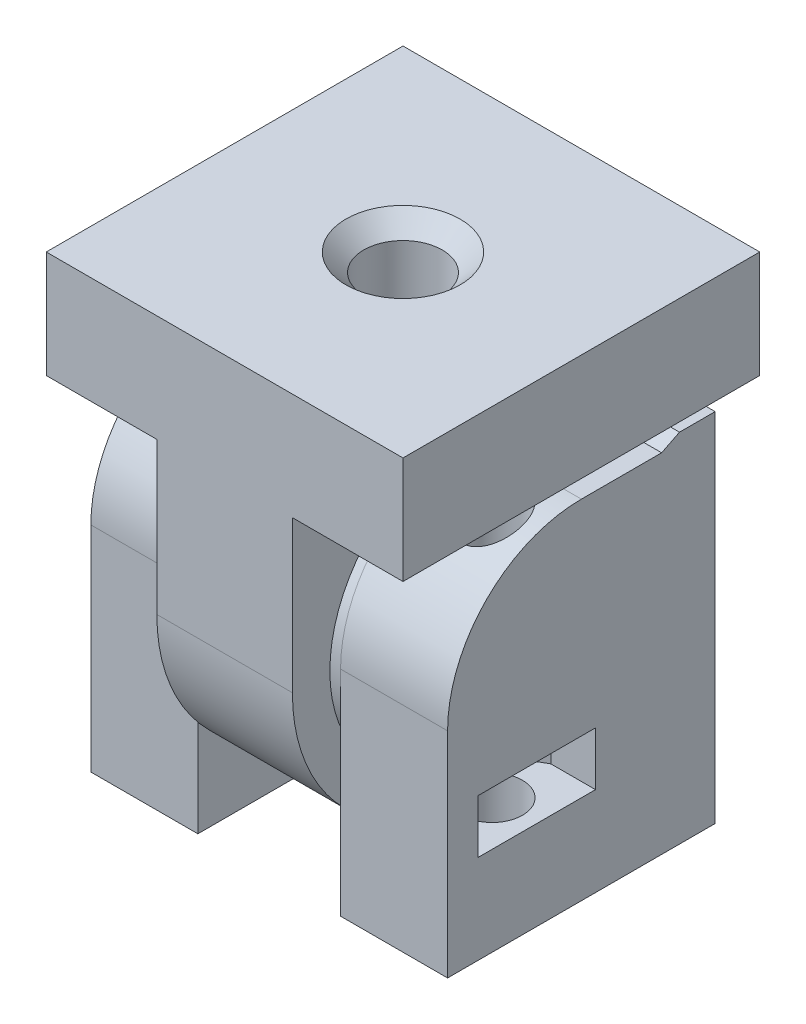
SolidWorks part; units mm, degrees
ref_plane "Front Plane" through (0, 0, 0) normal (0, 0, 1) x (1, 0, 0)
ref_plane "Top Plane" through (0, 0, 0) normal (0, 1, 0) x (1, 0, 0)
ref_plane "Right Plane" through (0, 0, 0) normal (1, 0, 0) x (0, 0, -1)
sketch "Sketch1" plane through (0, 0, 0) normal (1, 0, 0) x (0, 0, -1)
  circle A0 centre (0, 0) radius 7.5
  dimension "D1" = 15
extrude "Boss-Extrude1" add sketch "Sketch1" along normal blind 20
sketch "Sketch2" plane through (20, 0, 0) normal (1, 0, 0) x (0, 0, -1)
  line L5 (-7.5, 7.5) -> (7.5, 7.5)
  line L6 (-7.5, 7.5) -> (-7.5, -12)
  line L7 (-7.5, -12) -> (7.5, -12)
  line L8 (7.5, 7.5) -> (7.5, -12)
  circle A0 centre (0, 0) radius 7.5 construction
  point P0 (0, 0)
  point P6 (11.7696, -19.9449)
  point P7 (0, 7.5)
  point P10 (10, -14.5972)
  dimension "D1" = 12
extrude "Boss-Extrude2" add sketch "Sketch2" against normal blind 6
fillet "Fillet1" radius 7.5 1 edges at (17, 7.5, 7.5)
ref_plane "Plane3" through (10, 0, 0) normal (-1, 0, 0) x (0, 0, 1)
mirror "Mirror2" about plane through (10, 0, 0) normal (-1, 0, 0) of "Boss-Extrude2"
fillet "Fillet2" radius 7.5 1 edges at (3, 7.5, 7.5)
sketch "Sketch3" plane through (0, 7.5, 0) normal (0, 1, 0) x (1, 0, 0)
  line L0 (6, 7.5) -> (0, 7.5) construction
  line L1 (14, 7.5) -> (20, 7.5) construction
  circle A0 centre (3, -2.5) radius 1.7
  circle A1 centre (17, -2.5) radius 1.7
  point P6 (0, 0)
  point P9 (17, 7.5)
  point P10 (3, 7.5)
  dimension "D1" = 3.4
  dimension "D2" = 10
sketch "Sketch5" plane through (14, 0, 0) normal (-1, 0, 0) x (0, 0, 1)
  line L0 (10, 0) -> (10, 14.5)
  line L1 (10, 14.5) -> (-10, 14.5)
  line L2 (-7.5, 7.5) -> (0, 7.5) construction
  line L3 (-10, 0) -> (-10, 14.5)
  circle A0 centre (0, 0) radius 7.9
  circle A1 centre (0, 0) radius 7.5 construction
  circle A2 centre (0, 0) radius 10
  point P9 (13, 16.8825)
  line M5 (7.5, -12) -> (7.5, 0)
  line M15 (-7.5, 0) -> (-7.5, -12)
  dimension "D1" = 0.4
  dimension "D2" = 20
  dimension "D3" = 7
extrude "Boss-Extrude3" add sketch "Sketch5" along normal offset from surface (7.6 mm away) 0.2 from offset 0.2 separate body contours A2 A0 M15 M5 | A2 A0 M15 M5 | A2 L0 L1 L3 up to face at (6, -7.875, 0)
sketch "Sketch6" plane through (6.2, 0, 0) normal (-1, 0, 0) x (0, 0, 1)
  line L1 (10, 14.5) -> (-10, 14.5)
  line L2 (10, 14.5) -> (10, 8.5)
  line L3 (10, 8.5) -> (-10, 8.5)
  line L4 (-10, 14.5) -> (-10, 8.5)
  line L5 (-7.5, 7.5) -> (0, 7.5) construction
  line L7 (10, 14.5) -> (-10, 14.5) construction
  point P5 (-10.0218, 10.4)
  point P6 (-12.9171, 17)
  point P11 (-13, 17)
  dimension "D1" = 1
extrude "Boss-Extrude4" add sketch "Sketch6" along normal up to surface (6.2 mm away) contours L2 L1 L4 L3 up to face at (0, -1.4893, 0.3107)
sketch "Sketch7" plane through (13.8, 0, 0) normal (1, 0, 0) x (0, 0, -1)
  line L0 (-10, 0) -> (-10, 14.5) construction
  line L1 (10, 14.5) -> (-10, 14.5)
  line L2 (10, 14.5) -> (10, 8.5)
  line L3 (10, 8.5) -> (-10, 8.5)
  line L4 (-10, 14.5) -> (-10, 8.5)
  line L5 (7.5, 7.5) -> (0, 7.5) construction
  dimension "D1" = 1
extrude "Boss-Extrude5" add sketch "Sketch7" along normal up to surface (6.2 mm away) up to face at (20, -1.4893, 0.3107)
sketch "Sketch8" plane through (20, 0, 0) normal (1, 0, 0) x (0, 0, -1)
  line L0 (10, 14.5) -> (-10, 14.5) construction
  circle A0 centre (0, 11.5) radius 1.7
  point P2 (0, 0)
  dimension "D1" = 3.4
  dimension "D2" = 3
sketch "Sketch10" plane through (0, 14.5, 0) normal (0, 1, 0) x (1, 0, 0)
  line L0 (10, 8.25) -> (10, -8.25) construction
  line L1 (0, 10) -> (0, -10) construction
  circle A0 centre (10, 0) radius 2.2
  point P4 (0, 0)
  point P7 (0, 0)
  dimension "D1" = 4.4
extrude "Cut-Extrude6" cut sketch "Sketch10" against normal blind 7
chamfer "Chamfer2" distance 1 angle 45 1 edges at (10, 14.5, 2.2)
sketch "Sketch11" plane through (0, -12, 0) normal (0, -1, 0) x (-1, 0, 0)
  line L0 (-2.5, -2.5) -> (-10, -2.5)
  line L1 (-10, -8.25) -> (-10, 8.25) construction
  line L2 (-17.5, -2.5) -> (-10, -2.5)
  line L4 (-6, 7.5) -> (0, 7.5) construction
  circle A0 centre (-2.5, -2.5) radius 1.7
  circle A1 centre (-17.5, -2.5) radius 1.7
  dimension "D1" = 3.4
  dimension "D2" = 15
  dimension "D3" = 10
extrude "Cut-Extrude7" cut sketch "Sketch11" against normal blind 20
sketch "Sketch12" plane through (0, -12, 0) normal (0, -1, 0) x (-1, 0, 0)
  line L0 (-17.5, -5.7909) -> (-20, -5.7909)
  line L1 (-14.65, -4.1454) -> (-14.65, -0.8546)
  line L2 (-14.65, -0.8546) -> (-17.5, 0.7909)
  line L3 (-17.5, 0.7909) -> (-20.35, -0.8546)
  line L4 (-20.35, -0.8546) -> (-20.35, -4.1454)
  line L5 (-20.35, -4.1454) -> (-17.5, -5.7909)
  line L6 (-17.5, -5.7909) -> (-14.65, -4.1454)
  line L7 (-20, -7.5) -> (-20, 7.5) construction
  line L8 (-20, -5.7909) -> (-20, 0.7909)
  line L9 (-20, 1.7) -> (-20, -1.7) construction
  line L10 (-20, 0.7909) -> (-17.5, 0.7909)
  line L11 (-10, -8.25) -> (-10, 8.25) construction
  line L12 (0, 0.7909) -> (-2.5, 0.7909)
  line L13 (0, -5.7909) -> (0, 0.7909)
  line L14 (-2.5, -5.7909) -> (-5.35, -4.1454)
  line L15 (0.35, -4.1454) -> (-2.5, -5.7909)
  line L16 (0.35, -0.8546) -> (0.35, -4.1454)
  line L17 (-2.5, 0.7909) -> (0.35, -0.8546)
  line L18 (-5.35, -0.8546) -> (-2.5, 0.7909)
  line L19 (-5.35, -4.1454) -> (-5.35, -0.8546)
  line L20 (-2.5, -5.7909) -> (0, -5.7909)
  circle A0 centre (-17.5, -2.5) radius 2.85 construction
  circle A1 centre (-2.5, -2.5) radius 2.85 construction
  circle M7 centre (-2.5, -2.5) radius 1.7
  line M8 (0, -7.5) -> (0, 7.5)
  dimension "D1" = 5.7
extrude "Cut-Extrude8" cut sketch "Sketch12" against normal blind 3 from offset 5 contours L19 L14 L15 L13 L17 L18 M7 | M7 | L15 L20 M8 | L12 L17 M8 | L8 L5 L6 L1 L2 L3 | L8 L0 L5 | L10 L8 L3 offset against normal yes
sketch "Sketch13" plane through (20, 0, 0) normal (1, 0, 0) x (0, 0, -1)
  line L0 (7.5, 7.5) -> (7.5, 8)
  line L1 (7.5, 8) -> (5.5, 8)
  line L2 (5.5, 8) -> (4.5, 7.5)
  line L3 (7.5, 7.5) -> (0, 7.5) construction
  line L4 (-10, 8.5) -> (10, 8.5) construction
  line L5 (4.5, 7.5) -> (7.5, 7.5)
  dimension "D1" = 0.5
  dimension "D2" = 2
  dimension "D3" = 3
extrude "Boss-Extrude6" add sketch "Sketch13" against normal up to surface (6 mm away) up to face at (14, 5.5178, -5.5178)
sketch "Sketch15" plane through (0, 0, 0) normal (-1, 0, 0) x (0, 0, 1)
  line L0 (-7.5, 7.5) -> (-7.5, 8)
  line L1 (-7.5, 8) -> (-5.5, 8)
  line L2 (-5.5, 8) -> (-4.5, 7.5)
  line L3 (-7.5, 7.5) -> (0, 7.5) construction
  line L4 (-4.5, 7.5) -> (-7.5, 7.5)
  line L5 (-10, 8.5) -> (10, 8.5) construction
  dimension "D1" = 0.5
  dimension "D2" = 2
  dimension "D3" = 3
extrude "Boss-Extrude7" add sketch "Sketch15" against normal up to surface (6 mm away) up to face at (6, -7.875, 0)
